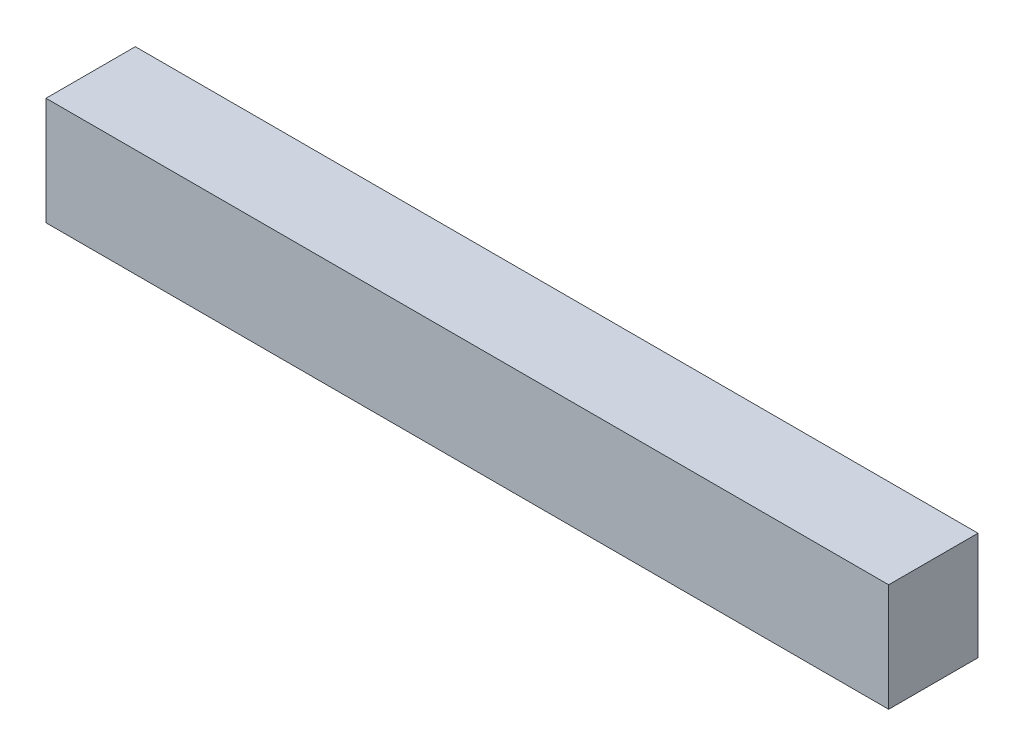
SolidWorks part; units mm, degrees
ref_plane "Front Plane" through (0, 0, 0) normal (0, 0, 1) x (1, 0, 0)
ref_plane "Top Plane" through (0, 0, 0) normal (0, 1, 0) x (1, 0, 0)
ref_plane "Right Plane" through (0, 0, 0) normal (1, 0, 0) x (0, 0, -1)
sketch "Sketch1" plane through (0, 0, 0) normal (0, 0, 1) x (1, 0, 0)
  line L1 (0, 0) -> (30, 0)
  line L2 (0, 0) -> (0, 3.84)
  line L3 (0, 3.84) -> (30, 3.84)
  line L4 (30, 0) -> (30, 3.84)
  dimension "D1" = 3.84
  dimension "D2" = 30
extrude "Boss-Extrude1" add sketch "Sketch1" along normal blind 3.18
